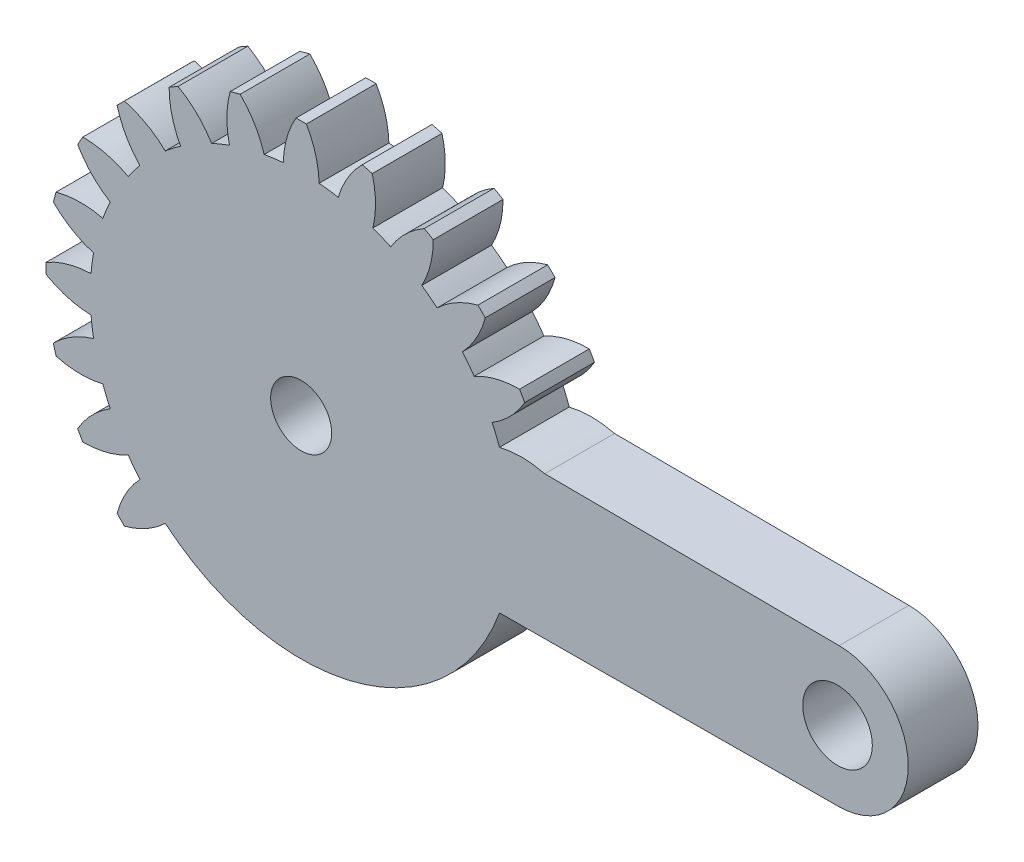
SolidWorks part; units mm, degrees
material "Acrylic (Medium-high impact)"
ref_plane "Front Plane" through (0, 0, 0) normal (0, 0, 1) x (1, 0, 0)
ref_plane "Top Plane" through (0, 0, 0) normal (0, 1, 0) x (1, 0, 0)
ref_plane "Right Plane" through (0, 0, 0) normal (1, 0, 0) x (0, 0, -1)
sketch "Sketch1" plane through (0, 0, 0) normal (0, 0, 1) x (1, 0, 0)
  line L0 (0, 0) -> (0, 8.7244) construction
  line L1 (0, 12.09) -> (0, 14.63) construction
  line L2 (0, 0) -> (30.75, 0) construction
  line L3 (11.3698, -4.1104) -> (30.8258, -3.9999)
  line L4 (30.8419, 3.9998) -> (11.3698, 4.1104)
  circle A0 centre (0, 0) radius 1.75
  circle A1 centre (0, 0) radius 12.09
  circle A2 centre (0, 0) radius 14.63
  arc A3 (0.297, 14.627) -> (1.0278, 12.0462) centre (-4.3706, 11.9115) cw
  arc A4 (-0.297, 14.627) -> (-1.0278, 12.0462) centre (4.3706, 11.9115) ccw
  arc A5 (3.4989, 14.2054) -> (2.1252, 11.9017) centre (7.3048, 10.3746) ccw
  arc A6 (4.0729, 14.0516) -> (4.1107, 11.3697) centre (-1.1385, 12.637) cw
  arc A7 (7.0563, 12.8158) -> (5.1333, 10.9461) centre (9.7413, 8.1307) ccw
  arc A8 (7.5712, 12.5185) -> (6.9135, 9.9183) centre (2.1713, 12.5012) cw
  arc A9 (10.1327, 10.5529) -> (7.7915, 9.2445) centre (11.514, 5.3326) ccw
  arc A10 (10.5534, 10.1322) -> (9.245, 7.791) centre (5.3331, 11.5135) cw
  arc A11 (12.5187, 7.571) -> (9.9186, 6.9129) centre (12.5021, 2.171) ccw
  arc A12 (12.8163, 7.0554) -> (10.9464, 5.1327) centre (8.1315, 9.7411) cw
  arc A13 (13.9662, 4.0956) -> (11.3698, 4.1104) centre (12.6382, -1.1386) ccw
  arc A14 (14.2057, 3.4978) -> (11.9018, 2.1248) centre (10.3759, 7.3047) cw
  arc A15 (14.627, 0.298) -> (12.0462, 1.0278) centre (11.9132, -4.3706) ccw
  arc A16 (14.627, -0.298) -> (12.0462, -1.0278) centre (11.9132, 4.3705) cw
  arc A17 (14.2058, -3.4976) -> (11.9018, -2.1248) centre (10.3763, -7.3048) ccw
  arc A18 (14.0515, -4.0735) -> (11.3698, -4.1104) centre (12.6387, 1.1384) cw
  arc A19 (12.8166, -7.0548) -> (10.9465, -5.1326) centre (8.1324, -9.7413) ccw
  arc A20 (12.5185, -7.5713) -> (9.9187, -6.9128) centre (12.5029, -2.1713) cw
  arc A21 (10.5542, -10.1314) -> (9.2453, -7.7906) centre (5.3343, -11.514) ccw
  arc A22 (10.1326, -10.5531) -> (7.7918, -9.2442) centre (11.5152, -5.3331) cw
  arc A23 (7.5727, -12.5176) -> (6.9141, -9.9178) centre (2.1727, -12.5021) ccw
  arc A24 (7.0562, -12.8159) -> (5.134, -10.9458) centre (9.7427, -8.1315) cw
  arc A25 (4.0751, -14.051) -> (4.1119, -11.3693) centre (-1.1369, -12.6383) ccw
  arc A26 (3.4992, -14.2054) -> (2.1264, -11.9015) centre (7.3064, -10.3759) cw
  arc A27 (0.2997, -14.6269) -> (1.0295, -12.0461) centre (-4.3689, -11.9132) ccw
  arc A28 (-0.2963, -14.627) -> (-1.0261, -12.0464) centre (4.3722, -11.9132) cw
  arc A29 (-3.4962, -14.2061) -> (-2.1232, -11.9021) centre (-7.3032, -10.3763) ccw
  arc A30 (-4.0716, -14.052) -> (-4.1088, -11.3704) centre (1.1401, -12.6387) cw
  arc A31 (-7.0539, -12.8171) -> (-5.1312, -10.9471) centre (-9.7397, -8.1324) ccw
  arc A32 (-7.5696, -12.5195) -> (-6.9116, -9.9196) centre (-2.1696, -12.5029) cw
  arc A33 (-10.131, -10.5546) -> (-7.7897, -9.246) centre (-11.5123, -5.3343) ccw
  arc A34 (-10.5518, -10.1339) -> (-9.2434, -7.7928) centre (-5.3314, -11.5152) cw
  arc A35 (-12.5176, -7.5727) -> (-9.9173, -6.9148) centre (-12.5004, -2.1727) ccw
  arc A36 (-12.815, -7.0577) -> (-10.9454, -5.1348) centre (-8.1299, -9.7428) cw
  arc A37 (-14.0511, -4.0746) -> (-11.3691, -4.1123) centre (-12.6366, 1.1368) ccw
  arc A38 (-14.205, -3.5005) -> (-11.9014, -2.1269) centre (-10.3742, -7.3064) cw
  arc A39 (-14.627, -0.2987) -> (-12.0461, -1.0294) centre (-11.9115, 4.3689) ccw
  arc A40 (-14.627, 0.2953) -> (-12.0464, 1.0261) centre (-11.9115, -4.3722) cw
  arc A41 (-14.2058, 3.4976) -> (-11.902, 2.1236) centre (-10.3746, 7.3031) ccw
  arc A42 (-14.0521, 4.0711) -> (-11.3703, 4.1092) centre (-12.637, -1.1401) cw
  arc A43 (-12.8163, 7.0554) -> (-10.9467, 5.132) centre (-8.1307, 9.7396) ccw
  arc A44 (-12.5195, 7.5696) -> (-9.9191, 6.9122) centre (-12.5013, 2.1696) cw
  arc A45 (-10.5533, 10.1324) -> (-9.2452, 7.7906) centre (-5.3326, 11.5123) ccw
  arc A46 (-10.1336, 10.5521) -> (-7.7919, 9.2442) centre (-11.5135, 5.3314) cw
  arc A47 (-7.571, 12.5187) -> (-6.9136, 9.9182) centre (-2.171, 12.5004) ccw
  arc A48 (-7.0569, 12.8155) -> (-5.1336, 10.946) centre (-9.7411, 8.1298) cw
  arc A49 (-4.0728, 14.0517) -> (-4.1108, 11.3697) centre (1.1385, 12.6366) ccw
  arc A50 (-3.4992, 14.2054) -> (-2.1253, 11.9017) centre (-7.3048, 10.3742) cw
  circle A51 centre (30.75, 0) radius 1.995
  arc A52 (30.8258, -3.9999) -> (30.8419, 3.9998) centre (30.8031, 0) ccw
  point P105 (0.0008, -0.0009)
  dimension "D1" = 3.5
  dimension "D2" = 24.18
  dimension "D3" = 29.26
  dimension "D4" = 5.4
  dimension "D7" = 3.99
  dimension "D8" = 4
  dimension "D5" = 24
  dimension "D6" = 30.75
extrude "Boss-Extrude1" add sketch "Sketch1" along normal blind 4 contours A1 A0 | L3 A52 L4 A2 A51 | A14 A2 L4 A1 | A36 A2 A35 A1 | A38 A2 A37 A1 | A40 A2 A39 A1 | A42 A2 A41 A1 | A44 A2 A43 A1 | A46 A2 A45 A1 | A48 A2 A47 A1 | A50 A2 A49 A1 | A2 A4 A1 A3 | A6 A2 A5 A1 | A8 A2 A7 A1 | A10 A2 A9 A1 | A12 A2 A11 A1 | A17 A2 A16 A1 | A18 A2 A17 A1 L3 | A16 A2 A15 A1 | A15 A2 A14 A1 | L4 A13 | A34 A2 A33 A1
